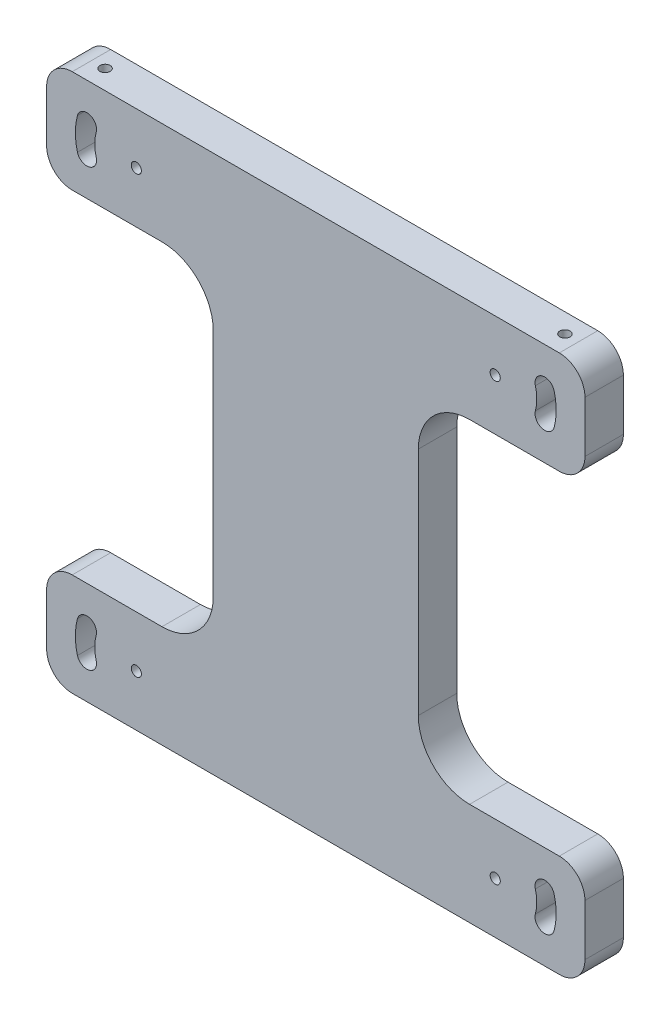
SolidWorks part; units mm, degrees
ref_plane "Front Plane" through (0, 0, 0) normal (0, 0, 1) x (1, 0, 0)
ref_plane "Top Plane" through (0, 0, 0) normal (0, 1, 0) x (1, 0, 0)
ref_plane "Right Plane" through (0, 0, 0) normal (1, 0, 0) x (0, 0, -1)
sketch "Model" plane through (0, 0, 0) normal (0, 0, 1) x (1, 0, 0)
  line L0 (332.9802, 413.0727) -> (91.6802, 413.0727)
  line L1 (345.6802, 374.9727) -> (345.6802, 400.3727)
  line L2 (288.5302, 362.2727) -> (332.9802, 362.2727)
  line L3 (263.1302, 222.5727) -> (263.1302, 336.8727)
  line L4 (332.9802, 197.1727) -> (288.5302, 197.1727)
  line L5 (345.6802, 159.0727) -> (345.6802, 184.4727)
  line L6 (91.6802, 146.3727) -> (332.9802, 146.3727)
  line L7 (78.9802, 184.4727) -> (78.9802, 159.0727)
  line L8 (136.1302, 197.1727) -> (91.6802, 197.1727)
  line L9 (161.5302, 336.8727) -> (161.5302, 222.5727)
  line L10 (91.6802, 362.2727) -> (136.1302, 362.2727)
  line L11 (78.9802, 400.3727) -> (78.9802, 374.9727)
  arc A0 (330.4023, 163.8881) -> (330.4023, 179.6574) centre (300.9762, 171.7727) ccw
  arc A1 (330.4023, 179.6574) -> (321.1098, 177.1675) centre (325.7561, 178.4125) ccw
  arc A2 (321.1098, 166.378) -> (321.1098, 177.1675) centre (300.9762, 171.7727) ccw
  arc A3 (321.1098, 166.378) -> (330.4023, 163.8881) centre (325.7561, 165.133) ccw
  arc A4 (103.5506, 177.1675) -> (103.5506, 166.378) centre (123.6842, 171.7727) ccw
  arc A5 (103.5506, 177.1675) -> (94.2581, 179.6574) centre (98.9043, 178.4125) ccw
  arc A6 (94.2581, 179.6574) -> (94.2581, 163.8881) centre (123.6842, 171.7727) ccw
  arc A7 (94.2581, 163.8881) -> (103.5506, 166.378) centre (98.9043, 165.133) ccw
  arc A8 (321.1098, 382.278) -> (321.1098, 393.0675) centre (300.9762, 387.6727) ccw
  arc A9 (321.1098, 382.278) -> (330.4023, 379.7881) centre (325.7561, 381.033) ccw
  arc A10 (330.4023, 379.7881) -> (330.4023, 395.5574) centre (300.9762, 387.6727) ccw
  arc A11 (330.4023, 395.5574) -> (321.1098, 393.0675) centre (325.7561, 394.3125) ccw
  arc A12 (94.2581, 395.5574) -> (94.2581, 379.7881) centre (123.6842, 387.6727) ccw
  arc A13 (94.2581, 379.7881) -> (103.5506, 382.278) centre (98.9043, 381.033) ccw
  arc A14 (103.5506, 393.0675) -> (103.5506, 382.278) centre (123.6842, 387.6727) ccw
  arc A15 (103.5506, 393.0675) -> (94.2581, 395.5574) centre (98.9043, 394.3125) ccw
  arc A16 (345.6802, 400.3727) -> (332.9802, 413.0727) centre (332.9802, 400.3727) ccw
  arc A17 (332.9802, 362.2727) -> (345.6802, 374.9727) centre (332.9802, 374.9727) ccw
  arc A18 (288.5302, 362.2727) -> (263.1302, 336.8727) centre (288.5302, 336.8727) ccw
  arc A19 (263.1302, 222.5727) -> (288.5302, 197.1727) centre (288.5302, 222.5727) ccw
  arc A20 (345.6802, 184.4727) -> (332.9802, 197.1727) centre (332.9802, 184.4727) ccw
  arc A21 (332.9802, 146.3727) -> (345.6802, 159.0727) centre (332.9802, 159.0727) ccw
  arc A22 (78.9802, 159.0727) -> (91.6802, 146.3727) centre (91.6802, 159.0727) ccw
  arc A23 (91.6802, 197.1727) -> (78.9802, 184.4727) centre (91.6802, 184.4727) ccw
  arc A24 (136.1302, 197.1727) -> (161.5302, 222.5727) centre (136.1302, 222.5727) ccw
  arc A25 (161.5302, 336.8727) -> (136.1302, 362.2727) centre (136.1302, 336.8727) ccw
  arc A26 (78.9802, 374.9727) -> (91.6802, 362.2727) centre (91.6802, 374.9727) ccw
  arc A27 (91.6802, 413.0727) -> (78.9802, 400.3727) centre (91.6802, 400.3727) ccw
  circle A28 centre (123.4302, 387.6727) radius 2.5146
  circle A29 centre (301.2302, 387.6727) radius 2.5146
  circle A30 centre (123.4302, 171.7727) radius 2.5146
  circle A31 centre (301.2302, 171.7727) radius 2.5146
extrude "Boss-Extrude1" add sketch "Model" along normal blind 19.05
sketch "Sketch2" plane through (0, 413.0727, 0) normal (0, 1, 0) x (1, 0, 0)
  line L0 (78.9802, -9.525) -> (345.6802, -9.525) construction
  line L1 (78.9802, -19.05) -> (78.9802, 0) construction
  line L2 (345.6802, -19.05) -> (345.6802, 0) construction
  line L3 (212.3302, 0) -> (212.3302, -19.05) construction
  line L4 (332.9802, 0) -> (91.6802, 0) construction
  line L5 (332.9802, -19.05) -> (91.6802, -19.05) construction
  circle A0 centre (98.4112, -9.525) radius 2.5527
  circle A1 centre (326.2492, -9.525) radius 2.5527
  dimension "D1" = 5.1054
  dimension "D2" = 19.431
extrude "Cut-Extrude1" cut sketch "Sketch2" against normal up to next
sketch "Sketch3" plane through (0, 146.3727, 0) normal (0, -1, 0) x (1, 0, 0)
  line L0 (78.9802, 9.525) -> (345.6802, 9.525) construction
  line L1 (78.9802, 19.05) -> (78.9802, 0) construction
  line L2 (345.6802, 19.05) -> (345.6802, 0) construction
  line L3 (212.3302, 19.05) -> (212.3302, 0) construction
  line L4 (91.6802, 19.05) -> (332.9802, 19.05) construction
  line L5 (91.6802, 0) -> (332.9802, 0) construction
  circle A0 centre (98.4112, 9.525) radius 2.5527
  circle A1 centre (326.2492, 9.525) radius 2.5527
  dimension "D1" = 5.1054
  dimension "D2" = 19.431
extrude "Cut-Extrude2" cut sketch "Sketch3" against normal up to next
